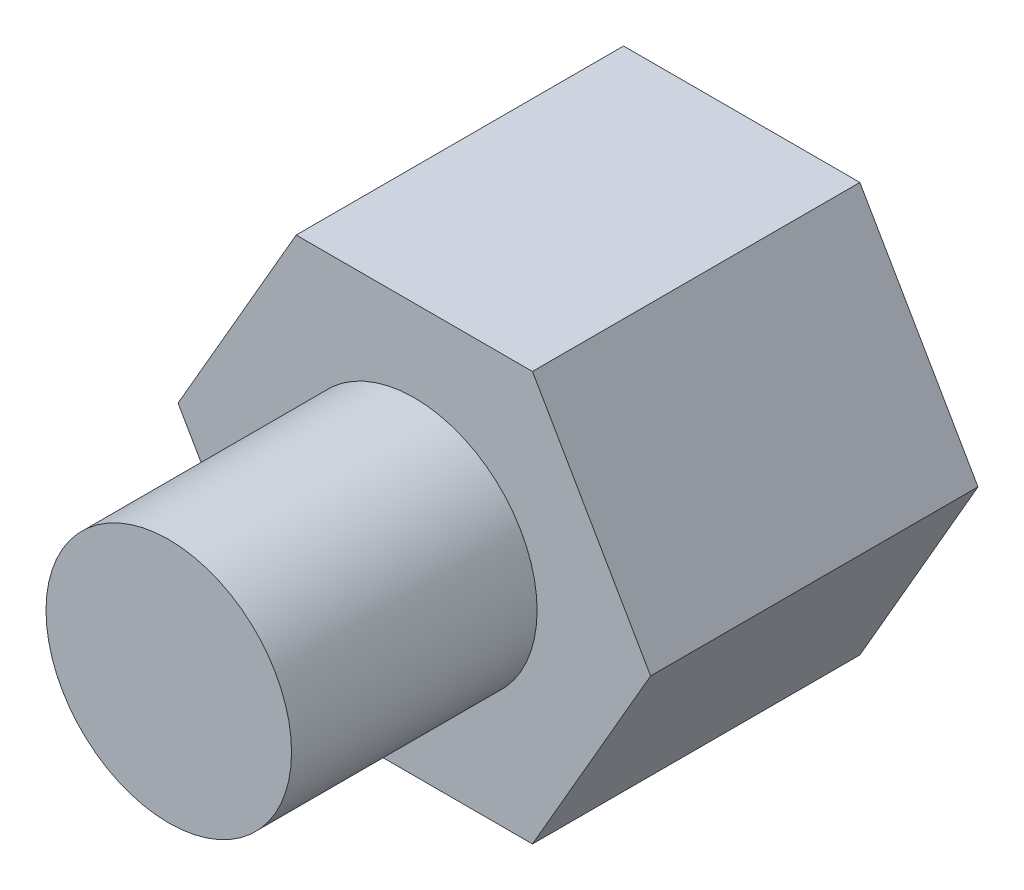
SolidWorks part; units mm, degrees
ref_plane "Front Plane" through (0, 0, 0) normal (0, 0, 1) x (1, 0, 0)
ref_plane "Top Plane" through (0, 0, 0) normal (0, 1, 0) x (1, 0, 0)
ref_plane "Right Plane" through (0, 0, 0) normal (1, 0, 0) x (0, 0, -1)
sketch "Sketch1" plane through (0, 0, 0) normal (0, 0, 1) x (1, 0, 0)
  line L1 (2.8868, 0) -> (1.4434, 2.5)
  line L2 (1.4434, 2.5) -> (-1.4434, 2.5)
  line L3 (-1.4434, 2.5) -> (-2.8868, 0)
  line L4 (-2.8868, 0) -> (-1.4434, -2.5)
  line L5 (-1.4434, -2.5) -> (1.4434, -2.5)
  line L6 (1.4434, -2.5) -> (2.8868, 0)
  circle A0 centre (0, 0) radius 2.5 construction
  point P1 (0, 0)
  dimension "D1" = 5
extrude "Boss-Extrude1" add sketch "Sketch1" along normal blind 4
sketch "Sketch2" plane through (0, 0, 0) normal (0, 0, -1) x (-1, 0, 0)
  circle A0 centre (0, 0) radius 1.5
  dimension "D1" = 3
extrude "Cut-Extrude1" cut sketch "Sketch2" against normal blind 3
sketch "Sketch3" plane through (0, 0, 4) normal (0, 0, 1) x (1, 0, 0)
  circle A0 centre (0, 0) radius 1.5
  dimension "D1" = 3
extrude "Boss-Extrude2" add sketch "Sketch3" along normal blind 3
